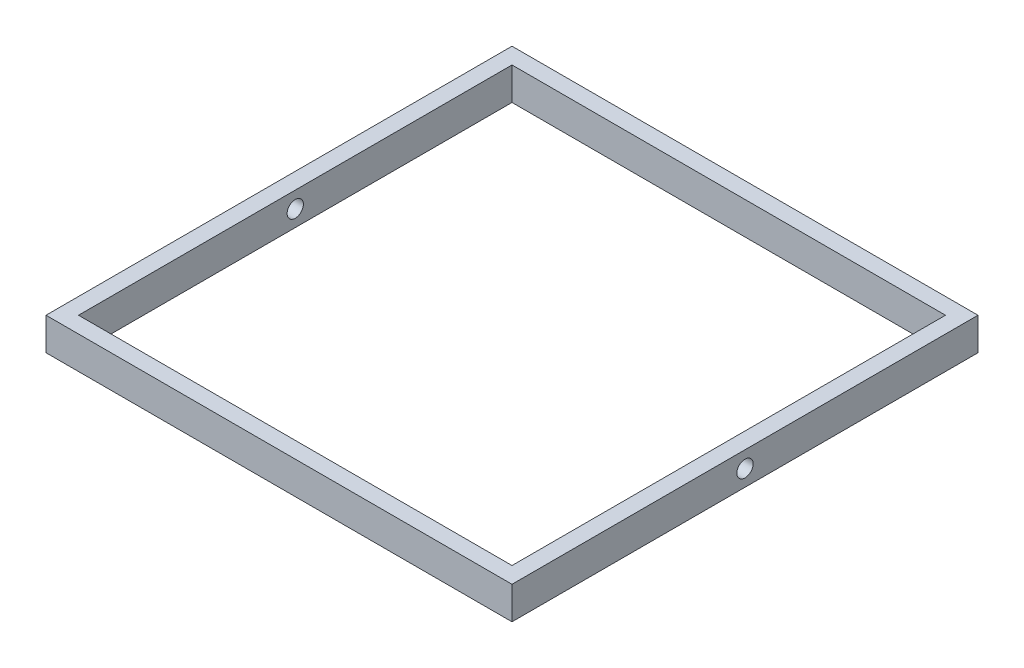
SolidWorks part; units mm, degrees
ref_plane "Front Plane" through (0, 0, 0) normal (0, 0, 1) x (1, 0, 0)
ref_plane "Top Plane" through (0, 0, 0) normal (0, 1, 0) x (1, 0, 0)
ref_plane "Right Plane" through (0, 0, 0) normal (1, 0, 0) x (0, 0, -1)
sketch "Sketch1" plane through (0, 0, 0) normal (0, 1, 0) x (1, 0, 0)
  line L0 (0.2206, 40) -> (-0.2206, -40) construction
  line L1 (-40.2206, -40) -> (39.7794, -40)
  line L2 (-40.2206, -40) -> (-40.2206, 40)
  line L3 (-40.2206, 40) -> (39.7794, 40)
  line L4 (39.7794, -40) -> (39.7794, 40)
  dimension "D1" = 80
  dimension "D2" = 80
extrude "Extrude-Thin1" add sketch "Sketch1" along normal blind 6 thin
sketch "Sketch2" plane through (39.7794, 0, 0) normal (-1, 0, 0) x (0, 0, 1)
  line L0 (-40, 3) -> (40, 3) construction
  line L1 (-40, 6) -> (-40, 0) construction
  line L2 (40, 6) -> (40, 0) construction
  circle A0 centre (0, 3) radius 1.5
  dimension "D1" = 3
extrude "Cut-Extrude1" cut sketch "Sketch2" against normal through all both and the other way through all
